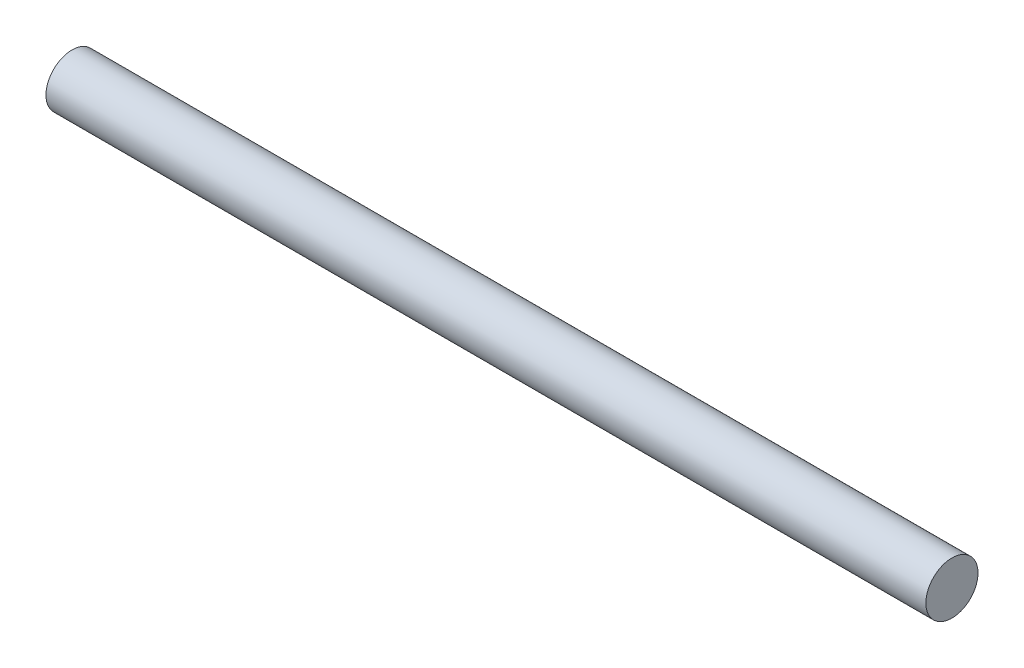
SolidWorks part; units mm, degrees
ref_plane "Front Plane" through (0, 0, 0) normal (0, 0, 1) x (1, 0, 0)
ref_plane "Top Plane" through (0, 0, 0) normal (0, 1, 0) x (1, 0, 0)
ref_plane "Right Plane" through (0, 0, 0) normal (1, 0, 0) x (0, 0, -1)
sketch "Sketch1" plane through (0, 0, 0) normal (1, 0, 0) x (0, 0, -1)
  circle A0 centre (0, 0) radius 4
  dimension "D1" = 8
extrude "Boss-Extrude1" add sketch "Sketch1" along normal blind 135
